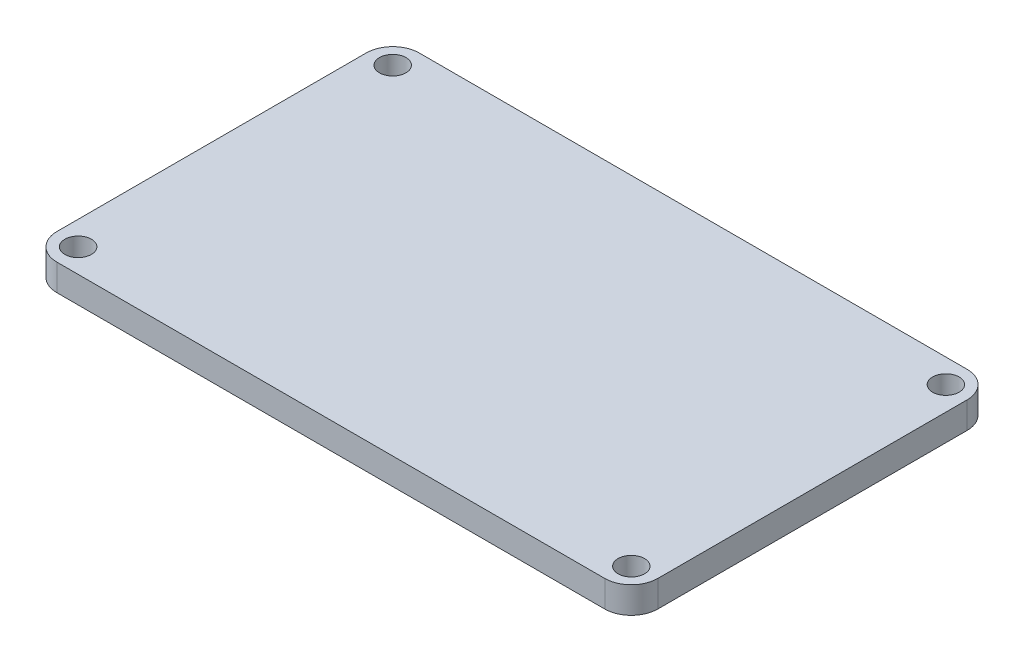
SolidWorks part; units mm, degrees
ref_plane "前视基准面" through (0, 0, 0) normal (0, 0, 1) x (1, 0, 0)
ref_plane "上视基准面" through (0, 0, 0) normal (0, 1, 0) x (1, 0, 0)
ref_plane "右视基准面" through (0, 0, 0) normal (1, 0, 0) x (0, 0, -1)
other "Configuration Table"
sketch "草图1" plane through (0, 0, 0) normal (0, 1, 0) x (1, 0, 0)
  line L1 (34, -20.5) -> (-34, -20.5)
  line L2 (34, -20.5) -> (34, 20.5)
  line L3 (34, 20.5) -> (-34, 20.5)
  line L4 (-34, -20.5) -> (-34, 20.5)
  line L5 (34, -20.5) -> (-34, 20.5) construction
  line L6 (34, 20.5) -> (-34, -20.5) construction
  point P0 (0, 0)
  dimension "D1" = 68
  dimension "D2" = 41
extrude "凸台-拉伸1" add sketch "草图1" along normal blind 3
sketch "草图2" plane through (0, 3, 0) normal (0, 1, 0) x (1, 0, 0)
  line L0 (34, -20.5) -> (34, 20.5) construction
  line L1 (-34, -20.5) -> (34, -20.5) construction
  line L2 (0, 20.5) -> (0, 0)
  line L4 (34, 20.5) -> (-34, 20.5) construction
  line L5 (0, 0) -> (6.8473, 0)
  circle A0 centre (31.3, -17.8) radius 1.5
  circle A1 centre (-31.3, -17.8) radius 1.5
  circle A2 centre (31.3, 17.8) radius 1.5
  circle A3 centre (-31.3, 17.8) radius 1.5
  dimension "D1" = 2.7
  dimension "D2" = 2.7
extrude "切除-拉伸1" cut sketch "草图2" against normal blind 3 contours A2 | A1 | A0 | A3
fillet "圆角1" radius 3 1 edges at (-34, 1.5, -20.5)
fillet "圆角2" radius 3 1 edges at (34, 1.5, -20.5)
fillet "圆角3" radius 3 1 edges at (-34, 1.5, 20.5)
fillet "圆角4" radius 3 1 edges at (34, 1.5, 20.5)
